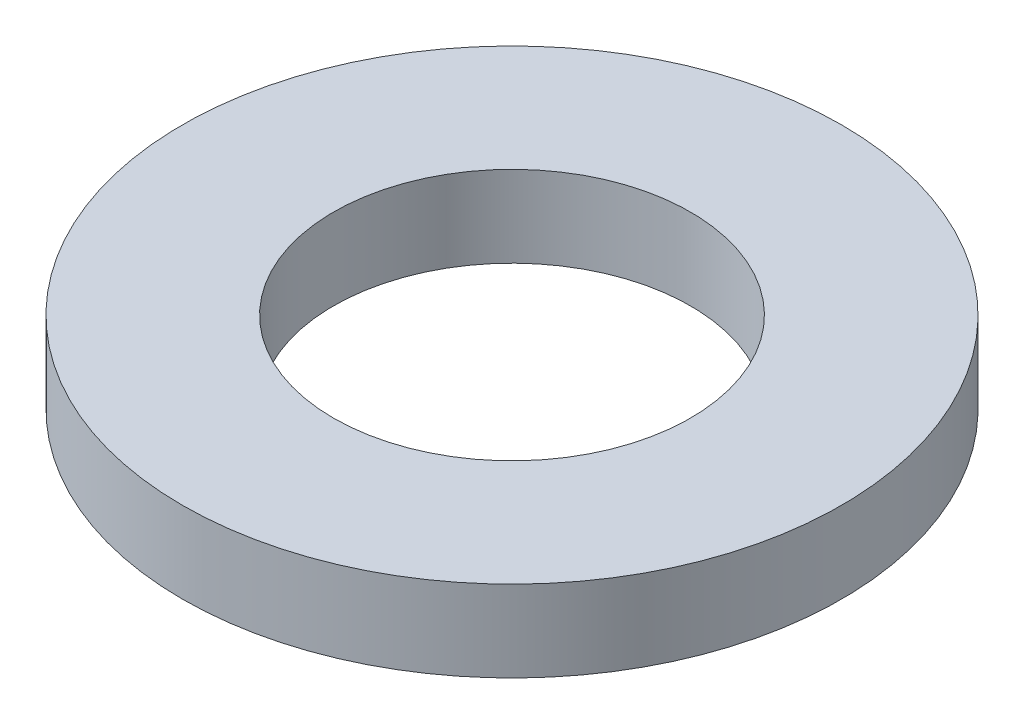
SolidWorks part; units mm, degrees
ref_plane "Front Plane" through (0, 0, 0) normal (0, 0, 1) x (1, 0, 0)
ref_plane "Top Plane" through (0, 0, 0) normal (0, 1, 0) x (1, 0, 0)
ref_plane "Right Plane" through (0, 0, 0) normal (1, 0, 0) x (0, 0, -1)
sketch "Sketch1" plane through (0, 0, 0) normal (0, 1, 0) x (1, 0, 0)
  circle A0 centre (0, 0) radius 6
  circle A1 centre (0, 0) radius 3.25
  dimension "D1" = 6.5
  dimension "D2" = 12
extrude "Boss-Extrude1" add sketch "Sketch1" along normal mid plane 1.48
